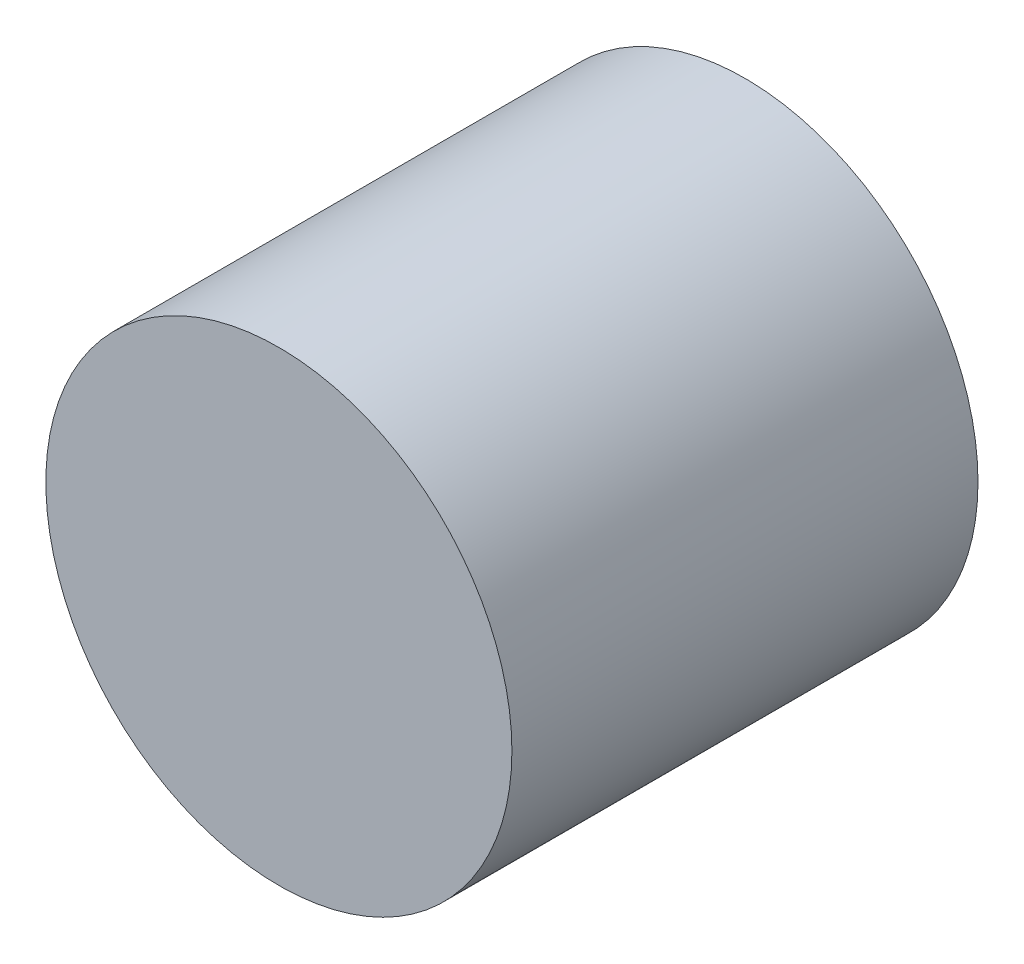
SolidWorks part; units mm, degrees
ref_plane "Plano frontal" through (0, 0, 0) normal (0, 0, 1) x (1, 0, 0)
ref_plane "Plano superior" through (0, 0, 0) normal (0, 1, 0) x (1, 0, 0)
ref_plane "Plano direito" through (0, 0, 0) normal (1, 0, 0) x (0, 0, -1)
sketch "Esboço1" plane through (0, 0, 0) normal (0, 0, 1) x (1, 0, 0)
  circle A0 centre (0, 0) radius 1
  dimension "D1" = 2
extrude "Ressalto-extrusão1" add sketch "Esboço1" along normal blind 2
